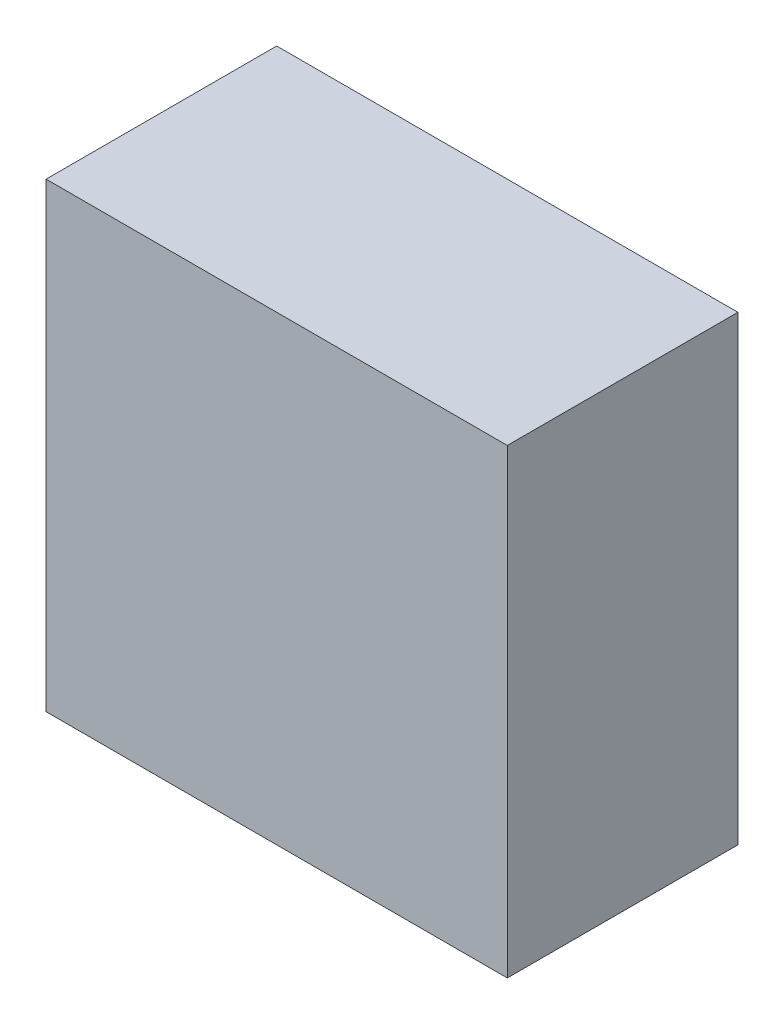
SolidWorks part; units mm, degrees
ref_plane "Front Plane" through (0, 0, 0) normal (0, 0, 1) x (1, 0, 0)
ref_plane "Top Plane" through (0, 0, 0) normal (0, 1, 0) x (1, 0, 0)
ref_plane "Right Plane" through (0, 0, 0) normal (1, 0, 0) x (0, 0, -1)
sketch "Sketch1" plane through (0, 0, 0) normal (0, 0, 1) x (1, 0, 0)
  line L1 (0, 0) -> (70, 0)
  line L2 (0, 0) -> (0, 70)
  line L3 (0, 70) -> (70, 70)
  line L4 (70, 0) -> (70, 70)
  dimension "D1" = 70
extrude "Boss-Extrude1" add sketch "Sketch1" along normal blind 35
